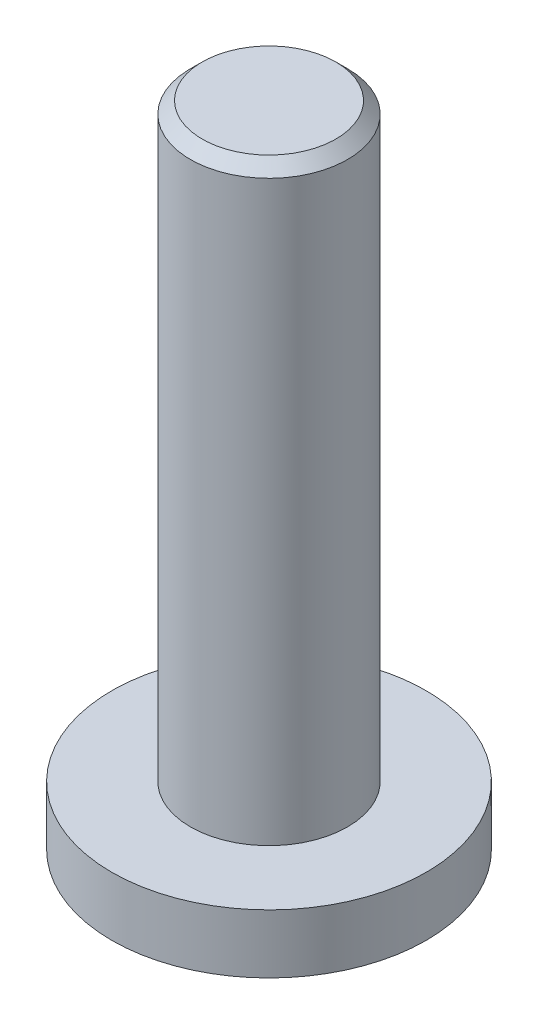
SolidWorks part; units mm, degrees
ref_plane "Спереди" through (0, 0, 0) normal (0, 0, 1) x (1, 0, 0)
ref_plane "Сверху" through (0, 0, 0) normal (0, 1, 0) x (1, 0, 0)
ref_plane "Справа" through (0, 0, 0) normal (1, 0, 0) x (0, 0, -1)
sketch "Эскиз1" plane through (0, 0, 0) normal (0, 1, 0) x (1, 0, 0)
  circle A0 centre (0, 0) radius 8
  dimension "D1" = 16
extrude "Бобышка-Вытянуть1" add sketch "Эскиз1" along normal blind 3
sketch "Эскиз2" plane through (0, 3, 0) normal (0, 1, 0) x (1, 0, 0)
  circle A0 centre (0, 0) radius 4
  dimension "D1" = 8
extrude "Бобышка-Вытянуть2" add sketch "Эскиз2" along normal blind 30
sketch "Эскиз3" plane through (0, 0, 0) normal (1, 0, 0) x (0, 0, -1)
  line L0 (-8, 0) -> (0, 2.1436)
  line L1 (0, 2.1436) -> (0, 0)
  line L2 (0, 0) -> (-8, 0)
  dimension "D1" = 15
revolve "Вырез-Повернуть1" cut sketch "Эскиз3" angle 360 about L1
chamfer "Фаска1" distance 0.6 angle 45 1 edges at (0, 33, 4)
